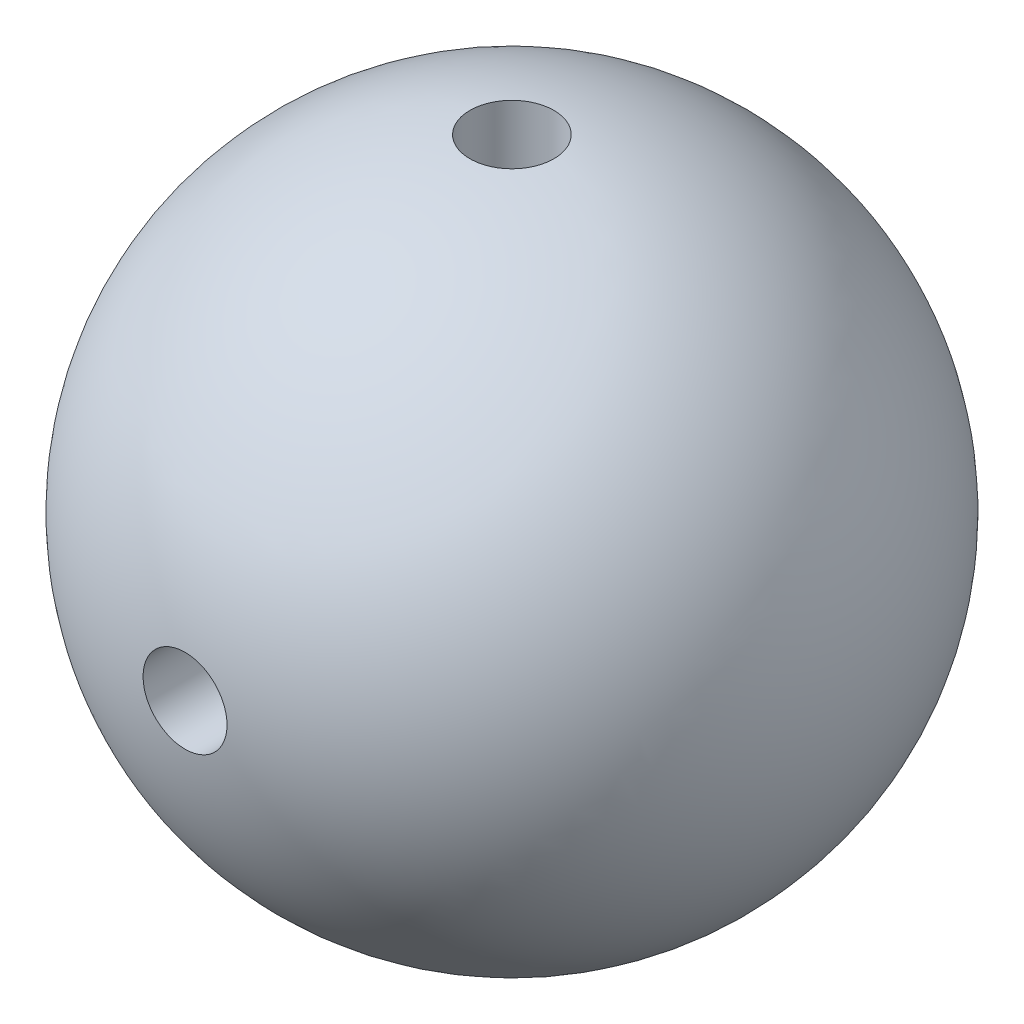
SolidWorks part; units mm, degrees
ref_plane "Front Plane" through (0, 0, 0) normal (0, 0, 1) x (1, 0, 0)
ref_plane "Top Plane" through (0, 0, 0) normal (0, 1, 0) x (1, 0, 0)
ref_plane "Right Plane" through (0, 0, 0) normal (1, 0, 0) x (0, 0, -1)
sketch "Sketch2" plane through (0, 0, 0) normal (0, 1, 0) x (1, 0, 0)
  line L0 (0, 7.85) -> (0, -7.85)
  arc A0 (0, -7.85) -> (0, 7.85) centre (0, 0) ccw
  dimension "D1" = 7.85
  dimension "D2" = 15.7
revolve "Revolve1" add sketch "Sketch2" angle 360 about L0
sketch "Sketch3" plane through (0, 0, 0) normal (0, 1, 0) x (1, 0, 0)
  circle A0 centre (0, 0) radius 1
  dimension "D1" = 2
extrude "Cut-Extrude3" cut sketch "Sketch3" against normal up to surface and the other way up to surface
sketch "Sketch4" plane through (0, 0, 0) normal (0, 0, 1) x (1, 0, 0)
  circle A0 centre (0, 0) radius 1
  dimension "D1" = 2
extrude "Cut-Extrude4" cut sketch "Sketch4" against normal up to surface and the other way up to surface up to face at (0, 7.786, -1) other way up to face at (0, 7.786, -1)
